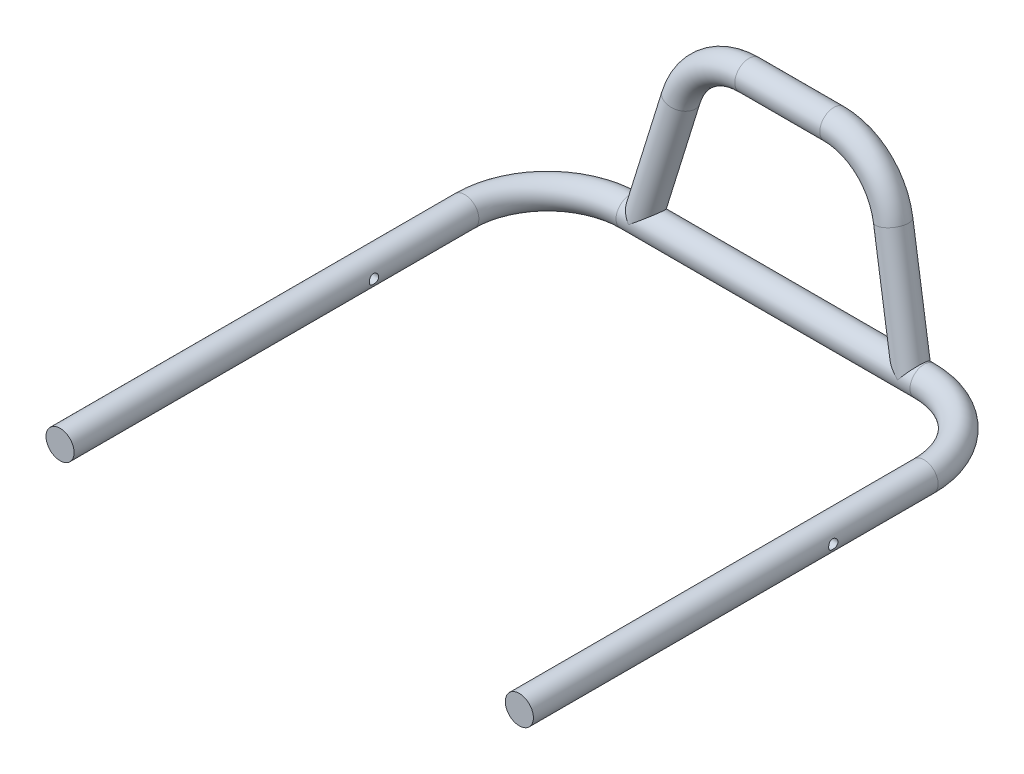
SolidWorks part; units mm, degrees
ref_plane "Front Plane" through (0, 0, 0) normal (0, 0, 1) x (1, 0, 0)
ref_plane "Top Plane" through (0, 0, 0) normal (0, 1, 0) x (1, 0, 0)
ref_plane "Right Plane" through (0, 0, 0) normal (1, 0, 0) x (0, 0, -1)
sketch "Sketch1" plane through (0, 0, 0) normal (0, 1, 0) x (1, 0, 0)
  line L0 (0, -8028.9326) -> (0, 393417.6977) construction
  line L1 (0, 330.2) -> (-99.575, 330.2)
  line L2 (-155.575, 274.2) -> (-155.575, 0)
  line L3 (0, 0) -> (-155.575, 0) construction
  line L4 (-146.05, 0) -> (-146.05, 330.2) construction
  line L5 (-165.1, 0) -> (-165.1, 330.2) construction
  arc A0 (-99.575, 330.2) -> (-155.575, 274.2) centre (-99.575, 274.2) ccw
  point P14 (-155.575, 330.2)
  point P15 (-155.575, 203.2)
  dimension "D5" = 56
  dimension "D1" = 330.2
  dimension "D2" = 19.05
  dimension "D3" = 9.525
  dimension "D4" = 146.05
  dimension "D6" = 203.2
ref_plane "Plane1" through (0, -28.6693, -327.6918) normal (0, 0.0872, 0.9962) x (-1, 0, 0)
sketch "Sketch2" plane through (0, -28.6693, -327.6918) normal (0, 0.0872, 0.9962) x (-1, 0, 0)
  line L0 (0, -28.7788) -> (0, -139.6836) construction
  line L1 (0, -139.6836) -> (28.7719, -139.6836)
  line L2 (71.9015, -105.9871) -> (91.1517, -28.7788)
  line L3 (0, -28.7788) -> (99.575, -28.7788) construction
  line L4 (0, 18130.9161) -> (0, -43577.8714) construction
  arc A0 (28.7719, -139.6836) -> (71.9015, -105.9871) centre (28.7719, -95.2336) ccw
  point P6 (0, 0)
  point P13 (63.5, -139.6836)
  dimension "D4" = 44.45
  dimension "D1" = 114.3
  dimension "D2" = 63.5
  dimension "D3" = 76
sweep "Sweep1" add path "Sketch2" circular profile diameter 19.05 parameters "D3"=19.05
sweep "Sweep2" add path "Sketch1" circular profile diameter 19.05 parameters "D3"=19.05
sketch "Sketch37" plane through (0, 0, 0) normal (1, 0, 0) x (0, 0, -1)
  circle A0 centre (203.2, 0) radius 3.175
  point P0 (203.2, 0)
  dimension "D1" = 6.35
extrude "Cut-Extrude1" cut sketch "Sketch37" against normal through all
mirror "Mirror1" about plane through (0, 0, 0) normal (1, 0, 0) of "Sweep1", "Sweep2", "Cut-Extrude1"
equation "\"bar_dia\"= 0.75in"
equation "\"D2@Sketch1\"=\"bar_dia\""
equation "\"D3@Sketch1\"=\"bar_dia\"/2"
equation "\"D2@Sketch2\"=5/2"
equation "\"D3@Sweep1\"=\"bar_dia\""
equation "\"D3@Sweep2\"=\"bar_dia\""
